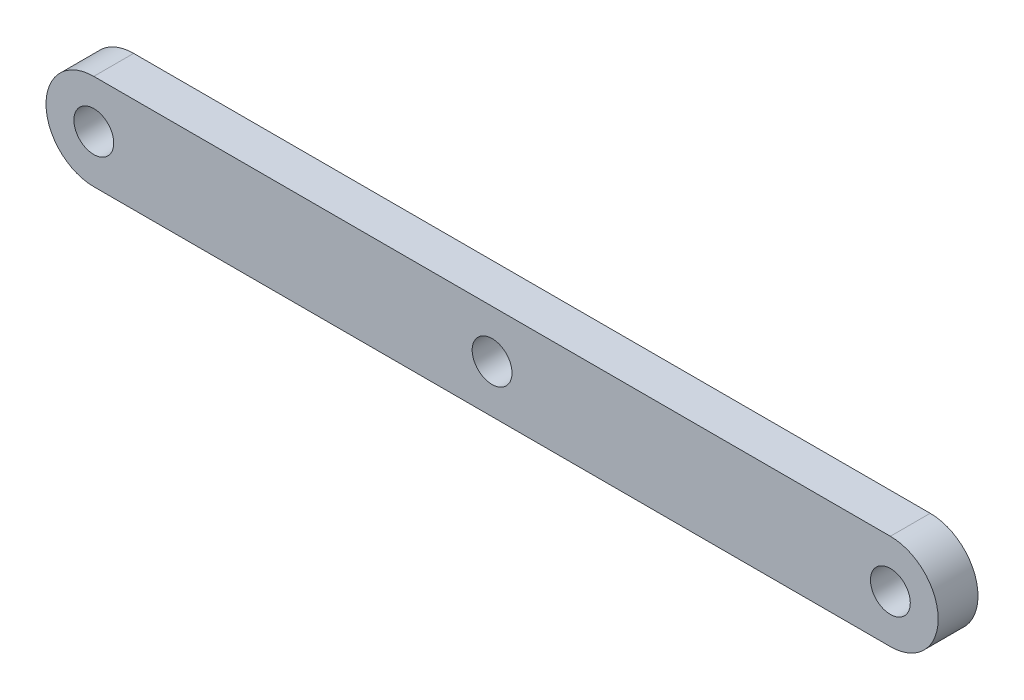
SolidWorks part; units mm, degrees
material "Acrylic (Medium-high impact)"
ref_plane "Front Plane" through (0, 0, 0) normal (0, 0, 1) x (1, 0, 0)
ref_plane "Top Plane" through (0, 0, 0) normal (0, 1, 0) x (1, 0, 0)
ref_plane "Right Plane" through (0, 0, 0) normal (1, 0, 0) x (0, 0, -1)
sketch "Sketch1" plane through (0, 0, 0) normal (0, 0, 1) x (1, 0, 0)
  line L0 (-50, 0) -> (50, 0) construction
  line L1 (-50, 6) -> (50, 6)
  line L2 (-50, -6) -> (50, -6)
  arc A0 (-50, 6) -> (-50, -6) centre (-50, 0) ccw
  arc A1 (50, -6) -> (50, 6) centre (50, 0) ccw
  circle A2 centre (-50, 0) radius 2.5
  circle A3 centre (50, 0) radius 2.5
  circle A4 centre (0, 0) radius 2.5
  point P2 (0, 0)
  dimension "D3" = 5
  dimension "D1" = 100
  dimension "D2" = 12
extrude "Boss-Extrude1" add sketch "Sketch1" along normal mid plane 5
